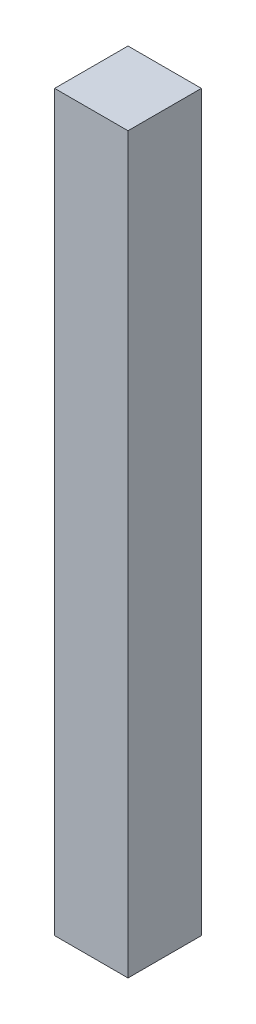
SolidWorks part; units mm, degrees
ref_plane "前视基准面" through (0, 0, 0) normal (0, 0, 1) x (1, 0, 0)
ref_plane "上视基准面" through (0, 0, 0) normal (0, 1, 0) x (1, 0, 0)
ref_plane "右视基准面" through (0, 0, 0) normal (1, 0, 0) x (0, 0, -1)
other "Configuration Table"
sketch "草图1" plane through (0, 0, 0) normal (0, 1, 0) x (1, 0, 0)
  line L1 (-10, 10) -> (10, 10)
  line L2 (-10, 10) -> (-10, -10)
  line L3 (-10, -10) -> (10, -10)
  line L4 (10, 10) -> (10, -10)
  line L5 (-10, 10) -> (10, -10) construction
  line L6 (-10, -10) -> (10, 10) construction
  point P0 (0, 0)
  dimension "D1" = 20
  dimension "D2" = 20
extrude "凸台-拉伸1" add sketch "草图1" along normal blind 200
